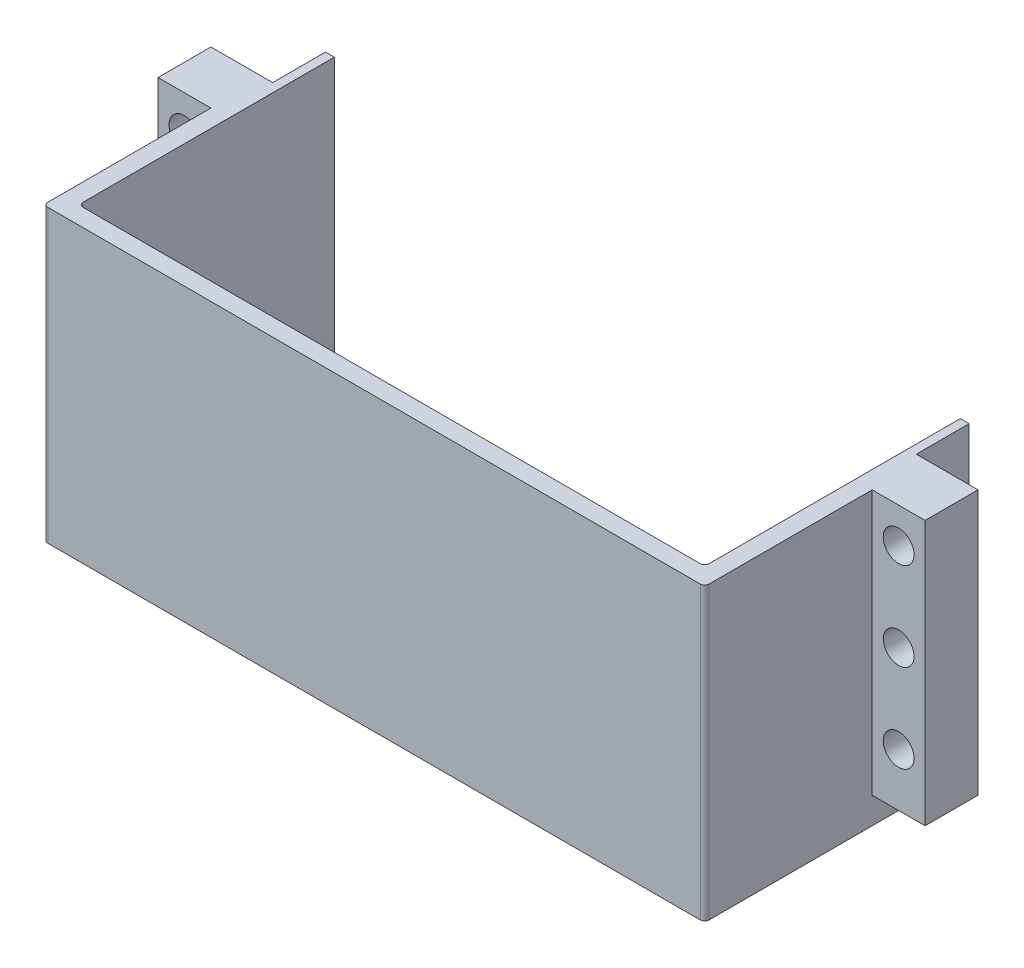
SolidWorks part; units mm, degrees
ref_plane "Front Plane" through (0, 0, 0) normal (0, 0, 1) x (1, 0, 0)
ref_plane "Top Plane" through (0, 0, 0) normal (0, 1, 0) x (1, 0, 0)
ref_plane "Right Plane" through (0, 0, 0) normal (1, 0, 0) x (0, 0, -1)
sketch "Sketch2" plane through (0, 0, 0) normal (0, 1, 0) x (1, 0, 0)
  line L0 (-37.5, 0) -> (37.5, 0) construction
  line L2 (-37.5, 0) -> (37.5, 0)
  line L3 (-37.5, 0) -> (-37.5, 25)
  line L4 (-37.5, 25) -> (37.5, 25)
  line L5 (37.5, 0) -> (37.5, 25)
  point P4 (0, 0)
extrude "Boss-Extrude1" add sketch "Sketch2" along normal blind 3
sketch "Sketch3" plane through (0, 3, 0) normal (0, 1, 0) x (1, 0, 0)
  line L0 (-35.5, 25) -> (-35.5, 2)
  line L1 (37.5, 25) -> (-37.5, 25) construction
  line L2 (-35.5, 2) -> (35.5, 2)
  line L3 (35.5, 2) -> (35.5, 25)
  line L4 (-37.5, 25) -> (-37.5, 0) construction
  line L5 (-37.5, 0) -> (37.5, 0) construction
  line L6 (37.5, 0) -> (37.5, 25) construction
  line L7 (-35.5, 25) -> (-37.5, 25)
  line L8 (-37.5, 25) -> (-37.5, 0)
  line L9 (-37.5, 0) -> (37.5, 0)
  line L10 (37.5, 0) -> (37.5, 25)
  line L11 (37.5, 25) -> (35.5, 25)
  dimension "D1" = 2
  dimension "D2" = 2
  dimension "D3" = 2
extrude "Boss-Extrude2" add sketch "Sketch3" along normal blind 30
sketch "Sketch4" plane through (37.5, 0, 0) normal (1, 0, 0) x (0, 0, -1)
  line L1 (25, 33) -> (19, 33)
  line L2 (25, 33) -> (25, 3)
  line L3 (25, 3) -> (19, 3)
  line L4 (19, 33) -> (19, 3)
  dimension "D1" = 6
  dimension "D2" = 30
extrude "Boss-Extrude3" add sketch "Sketch4" along normal blind 6
sketch "Sketch5" plane through (-37.5, 0, 0) normal (-1, 0, 0) x (0, 0, 1)
  line L1 (-25, 33) -> (-19, 33)
  line L2 (-25, 33) -> (-25, 3)
  line L3 (-25, 3) -> (-19, 3)
  line L4 (-19, 33) -> (-19, 3)
  dimension "D1" = 6
  dimension "D2" = 30
extrude "Boss-Extrude4" add sketch "Sketch5" along normal blind 6
sketch "Sketch6" plane through (0, 0, -25) normal (0, 0, -1) x (-1, 0, 0)
  line L0 (-40.5, 33) -> (-40.5, 3) construction
  line L1 (-43.5, 33) -> (-35.5, 33) construction
  line L2 (-43.5, 3) -> (-37.5, 3) construction
  line L3 (40.5, 33) -> (40.5, 3) construction
  line L4 (35.5, 33) -> (43.5, 33) construction
  line L5 (43.5, 3) -> (37.5, 3) construction
  line L6 (-43.5, 3) -> (-43.5, 33) construction
  line L7 (43.5, 33) -> (43.5, 3) construction
  circle A0 centre (-40.5, 29) radius 1.75
  circle A1 centre (40.5, 29) radius 1.75
  circle A2 centre (-40.5, 19) radius 1.75
  circle A3 centre (-40.5, 9) radius 1.75
  circle A4 centre (40.5, 19) radius 1.75
  circle A5 centre (40.5, 9) radius 1.75
  dimension "D5" = 3.5
  dimension "D6" = 3.5
  dimension "D1" = 3
  dimension "D2" = 3
  dimension "D3" = 4
  dimension "D4" = 4
  dimension "D7" = 3
  dimension "D8" = 3
extrude "Cut-Extrude1" cut sketch "Sketch6" against normal blind 16
sketch "Sketch7" plane through (0, 0, -25) normal (0, 0, -1) x (-1, 0, 0)
  line L0 (0, 0) -> (0, 3) construction
  line L17 (35.5, 33) -> (36.5, 33)
  line L18 (35.5, 33) -> (35.5, 3)
  line L20 (36.5, 33) -> (36.5, 2)
  line L21 (-35.5, 3) -> (35.5, 3) construction
  line L23 (-36.5, 33) -> (-36.5, 2)
  line L24 (-35.5, 33) -> (-36.5, 33)
  line L25 (-35.5, 33) -> (-35.5, 3)
  line L26 (-36.5, 2) -> (36.5, 2)
  line L27 (-35.5, 3) -> (35.5, 3)
  dimension "D1" = 1
  dimension "D2" = 31
extrude "Boss-Extrude5" add sketch "Sketch7" along normal blind 6
fillet "Fillet1" radius 0.5 2 edges at (35.5, 18, -2) (-35.5, 18, -2)
fillet "Fillet2" radius 0.5 2 edges at (37.5, 16.5, 0) (-37.5, 16.5, 0)
